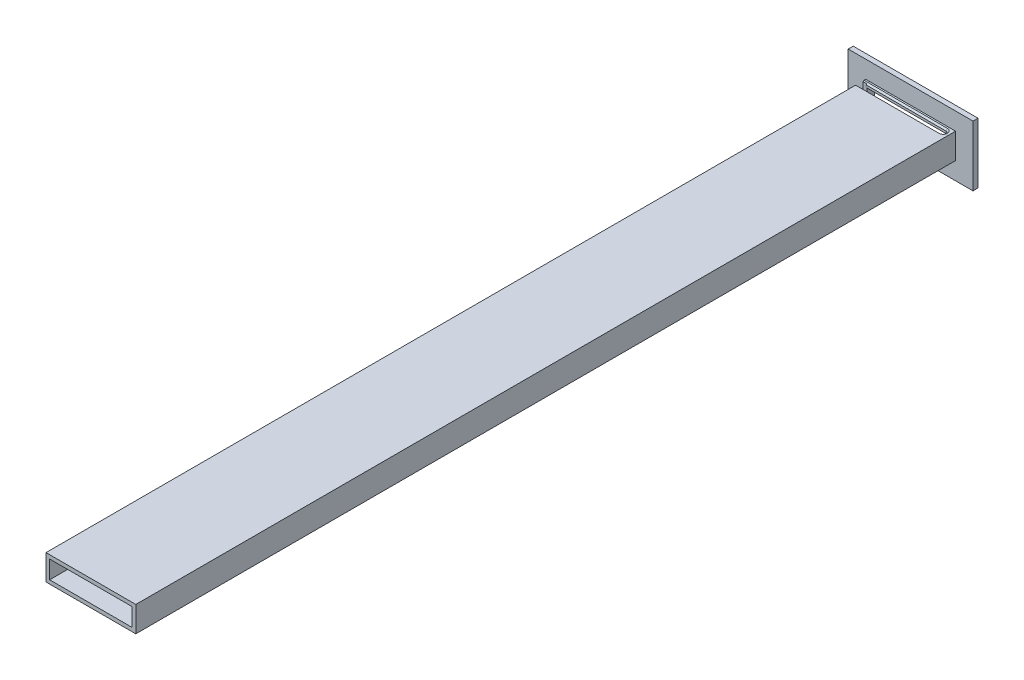
SolidWorks part; units mm, degrees
ref_plane "Piano frontale" through (0, 0, 0) normal (0, 0, 1) x (1, 0, 0)
ref_plane "Piano superiore" through (0, 0, 0) normal (0, 1, 0) x (1, 0, 0)
ref_plane "Piano destro" through (0, 0, 0) normal (1, 0, 0) x (0, 0, -1)
sketch "Schizzo1" plane through (0, 0, 0) normal (0, 0, 1) x (1, 0, 0)
  line L1 (-17.9659, 5.1) -> (17.9659, 5.1)
  line L2 (-17.9659, 5.1) -> (-17.9659, -5.1)
  line L3 (-17.9659, -5.1) -> (17.9659, -5.1)
  line L4 (17.9659, 5.1) -> (17.9659, -5.1)
  line L5 (-17.9659, 5.1) -> (17.9659, -5.1) construction
  line L6 (-17.9659, -5.1) -> (17.9659, 5.1) construction
  line L7 (-16.5, 3.6) -> (16.5, 3.6)
  line L8 (-16.5, 3.6) -> (-16.5, -3.6)
  line L9 (-16.5, -3.6) -> (16.5, -3.6)
  line L10 (16.5, 3.6) -> (16.5, -3.6)
  line L11 (-16.5, 3.6) -> (16.5, -3.6) construction
  line L12 (-16.5, -3.6) -> (16.5, 3.6) construction
  point P0 (0, 0)
  point P6 (0, 0)
  dimension "D1" = 1.5
  dimension "D2" = 7.2
  dimension "D3" = 33
extrude "Estrusione-Estrusione1" add sketch "Schizzo1" along normal blind 330
sketch "Schizzo3" plane through (-17.9659, 0, 0) normal (-1, 0, 0) x (0, 0, 1)
  line L0 (0, 0) -> (3, 0) construction
  line L2 (3, 3.6) -> (5.7, 3.6)
  line L3 (3, 3.6) -> (3, 0.4)
  line L4 (0, 3.6) -> (0, -3.6)
  line L5 (330, 3.6) -> (0, 3.6)
  line L6 (330, -3.6) -> (330, 3.6)
  line L7 (0, -3.6) -> (330, -3.6)
  line L8 (0, 3.6) -> (0, -3.6)
  line L9 (330, 3.6) -> (0, 3.6)
  line L10 (330, -3.6) -> (330, 3.6)
  line L11 (0, -3.6) -> (330, -3.6)
  line L12 (3, 0.4) -> (5.7, 0.4)
  line L13 (5.7, 3.6) -> (5.7, 0.4)
  dimension "D2" = 3
  dimension "D3" = 3.2
  dimension "D4" = 2.7
  dimension "D1" = 0
extrude "Taglio-Estrusione1" cut sketch "Schizzo3" against normal up to surface (34.4659 mm away) contours L13 L2 L3 L12 up to face at (16.5, 0, 165)
sketch "Schizzo4" plane through (0, 5.1, 0) normal (0, 1, 0) x (1, 0, 0)
  line L0 (-16.5, -4.35) -> (13.3, -4.35) construction
  line L1 (15.4, -5.45) -> (-17.9659, -5.45)
  line L2 (-17.9659, -330) -> (-17.9659, 0) construction
  line L3 (-17.9659, -5.45) -> (-17.9659, -3.25)
  line L4 (-16.5, -5.7) -> (-16.5, -3)
  line L5 (-16.5, -3) -> (-17.9659, -3)
  line L6 (-17.9659, -3) -> (-17.9659, -5.7)
  line L7 (-17.9659, -5.7) -> (-16.5, -5.7)
  line L8 (-16.5, -5.7) -> (-16.5, -3)
  line L9 (-16.5, -3) -> (-17.9659, -3)
  line L10 (-17.9659, -3) -> (-17.9659, -5.7)
  line L11 (-17.9659, -5.7) -> (-16.5, -5.7)
  line L12 (16.5, 0) -> (-16.5, 0)
  line L13 (-16.5, 0) -> (-16.5, -330)
  line L14 (-16.5, -330) -> (16.5, -330)
  line L15 (16.5, -330) -> (16.5, 0)
  line L16 (16.5, 0) -> (-16.5, 0)
  line L17 (-16.5, 0) -> (-16.5, -330)
  line L18 (-16.5, -330) -> (16.5, -330)
  line L19 (16.5, -330) -> (16.5, 0)
  line L20 (-17.9659, -3.25) -> (15.4, -3.25)
  arc A0 (15.4, -5.45) -> (15.4, -3.25) centre (15.4, -4.35) ccw
  dimension "D1" = 2.2
  dimension "D2" = 0
  dimension "D3" = 0
extrude "Taglio-Estrusione2" cut sketch "Schizzo4" against normal up to surface (1.5 mm away)
chamfer "Smusso2" distance 0.6 angle 45 3 edges at (-0.55, 5.1, 3.25) (16.5, 5.1, 4.35) (-0.55, 5.1, 5.45)
sketch "Schizzo5" plane through (0, 0, 0) normal (0, 0, -1) x (-1, 0, 0)
  line L0 (-17.9659, 5.1) -> (17.9659, 5.1) construction
  line L1 (-24.9659, -12.1) -> (24.9659, -12.1)
  line L2 (-24.9659, -12.1) -> (-24.9659, 12.1)
  line L3 (-24.9659, 12.1) -> (24.9659, 12.1)
  line L4 (24.9659, -12.1) -> (24.9659, 12.1)
  line L5 (-24.9659, -12.1) -> (24.9659, 12.1) construction
  line L6 (-24.9659, 12.1) -> (24.9659, -12.1) construction
  line L7 (17.9659, 5.1) -> (17.9659, -5.1) construction
  line L8 (17.9659, -5.1) -> (-17.9659, -5.1) construction
  line L9 (-17.9659, -5.1) -> (-17.9659, 5.1) construction
  line L10 (17.9659, 5.1) -> (17.9659, -5.1)
  line L11 (17.9659, -5.1) -> (-17.9659, -5.1)
  line L12 (-17.9659, -5.1) -> (-17.9659, 5.1)
  line L13 (-17.9659, 5.1) -> (17.9659, 5.1)
  point P0 (0, 0)
  dimension "D1" = 7
  dimension "D2" = 7
extrude "Estrusione-Estrusione2" add sketch "Schizzo5" against normal blind 2
